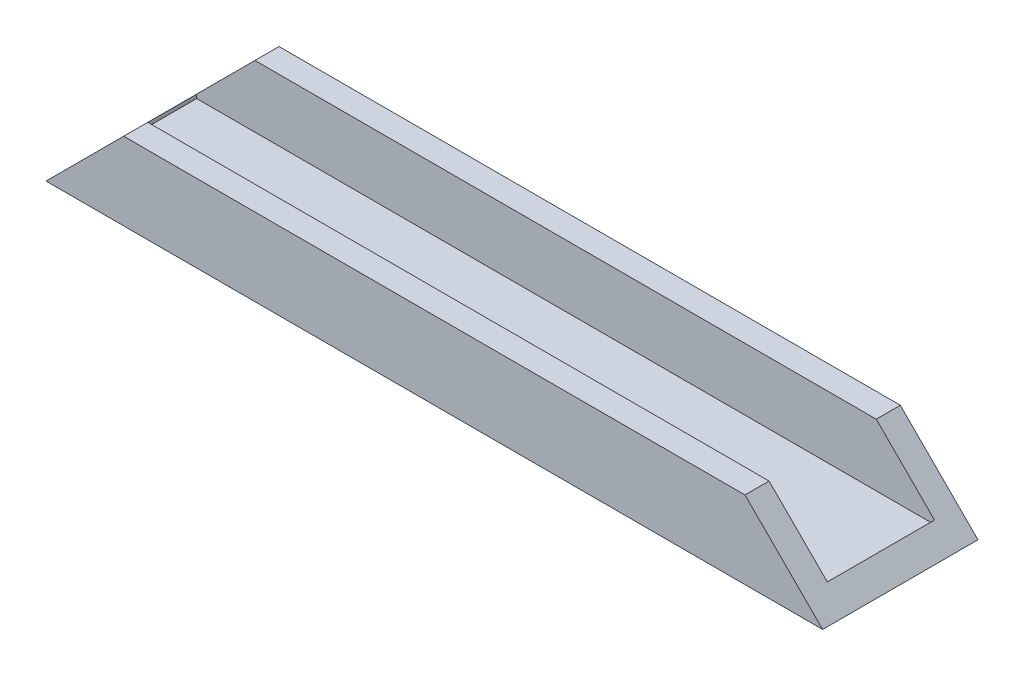
SolidWorks part; units mm, degrees
material "Copper"
ref_plane "Front Plane" through (0, 0, 0) normal (0, 0, 1) x (1, 0, 0)
ref_plane "Top Plane" through (0, 0, 0) normal (0, 1, 0) x (1, 0, 0)
ref_plane "Right Plane" through (0, 0, 0) normal (1, 0, 0) x (0, 0, -1)
sketch "Sketch1" plane through (0, 0, 0) normal (0, 1, 0) x (1, 0, 0)
  line L1 (0, 0) -> (127, 0)
  line L2 (0, 0) -> (0, 25.4)
  line L3 (0, 25.4) -> (127, 25.4)
  line L4 (127, 0) -> (127, 25.4)
  dimension "D1" = 127
  dimension "D2" = 25.4
extrude "Base Extrude" add sketch "Sketch1" along normal blind 12.7
sketch "Sketch3" plane through (0, 12.7, 0) normal (0, 1, 0) x (1, 0, 0)
  line L1 (3.175, 21.463) -> (123.825, 21.463)
  line L2 (3.175, 21.463) -> (3.175, 3.937)
  line L3 (3.175, 3.937) -> (123.825, 3.937)
  line L4 (123.825, 21.463) -> (123.825, 3.937)
  line L5 (0, 25.4) -> (0, 0) construction
  line L6 (127, 0) -> (127, 25.4) construction
  line L8 (3.175, 12.7) -> (123.825, 12.7) construction
  line L9 (127, 12.7) -> (0, 12.7) construction
  dimension "D1" = 17.526
  dimension "D3" = 3.175
  dimension "D4" = 3.175
extrude "Piece Cut" cut sketch "Sketch3" against normal blind 10.16
sketch "Sketch4" plane through (0, 0, -25.4) normal (0, 0, -1) x (-1, 0, 0)
  line L0 (0, 0) -> (-12.7, 12.7)
  line L1 (-127, 12.7) -> (0, 12.7) construction
  line L2 (0, 0) -> (0, 12.7)
  line L3 (0, 12.7) -> (-12.7, 12.7)
  line L4 (-63.5, 0) -> (-63.5, 12.7) construction
  line L5 (-127, 0) -> (0, 0) construction
  line L6 (-127, 12.7) -> (-114.3, 12.7)
  line L7 (-127, 0) -> (-127, 12.7)
  line L8 (-127, 0) -> (-114.3, 12.7)
  dimension "D1" = 45
extrude "Corner Cut" cut sketch "Sketch4" against normal through all
